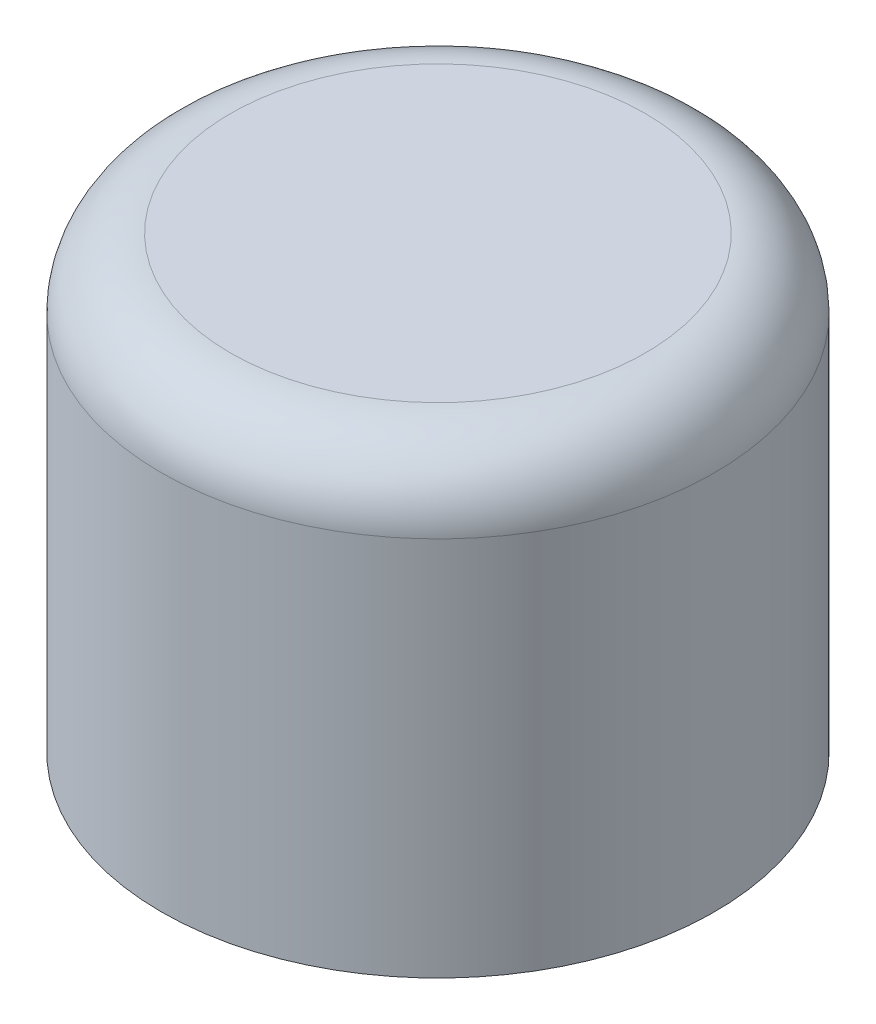
SolidWorks part; units mm, degrees
ref_plane "Front Plane" through (0, 0, 0) normal (0, 0, 1) x (1, 0, 0)
ref_plane "Top Plane" through (0, 0, 0) normal (0, 1, 0) x (1, 0, 0)
ref_plane "Right Plane" through (0, 0, 0) normal (1, 0, 0) x (0, 0, -1)
sketch "Sketch1" plane through (0, 0, 0) normal (0, 1, 0) x (1, 0, 0)
  circle A0 centre (0, 0) radius 10.16
extrude "Boss-Extrude2" add sketch "Sketch1" along normal blind 16.51 contours A0
sketch "Sketch2" plane through (0, 0, 0) normal (0, 1, 0) x (1, 0, 0)
  circle A0 centre (0, 0) radius 7.62
extrude "Cut-Extrude1" cut sketch "Sketch2" along normal blind 12.7 contours A0
fillet "Fillet2" radius 2.54 1 edges at (0, 16.51, 10.16)
